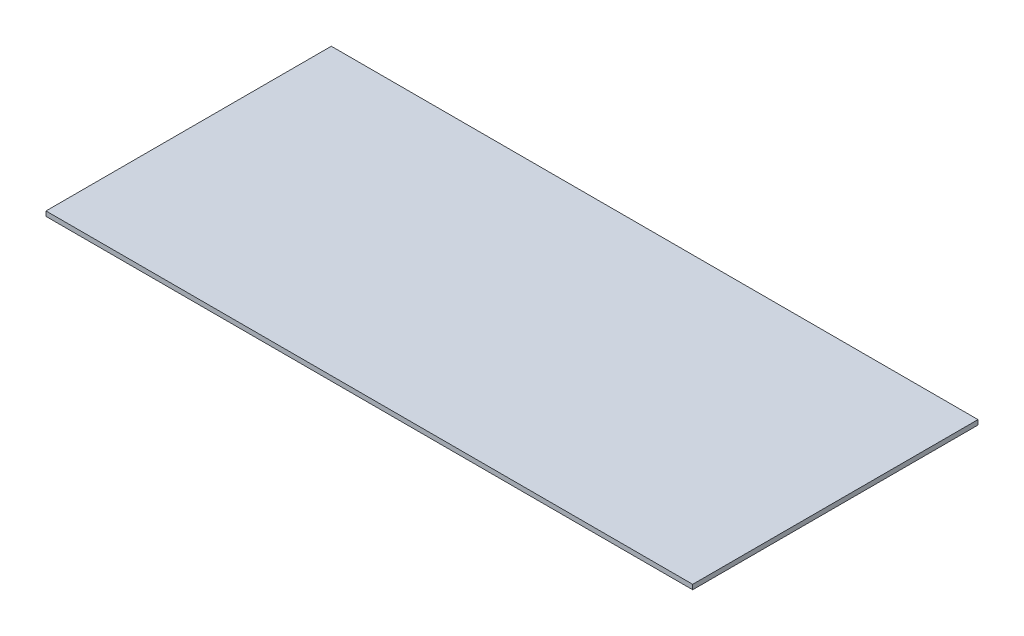
SolidWorks part; units mm, degrees
ref_plane "Ebene vorne" through (0, 0, 0) normal (0, 0, 1) x (1, 0, 0)
ref_plane "Ebene oben" through (0, 0, 0) normal (0, 1, 0) x (1, 0, 0)
ref_plane "Ebene rechts" through (0, 0, 0) normal (1, 0, 0) x (0, 0, -1)
sketch "Skizze1" plane through (0, 0, 0) normal (0, 1, 0) x (1, 0, 0)
  line L1 (-340, -150) -> (340, -150)
  line L2 (-340, -150) -> (-340, 150)
  line L3 (-340, 150) -> (340, 150)
  line L4 (340, -150) -> (340, 150)
  line L5 (-340, -150) -> (340, 150) construction
  line L6 (-340, 150) -> (340, -150) construction
  point P0 (0, 0)
  dimension "D1" = 680
  dimension "D2" = 300
extrude "Aufsatz-Linear austragen1" add sketch "Skizze1" along normal blind 5
